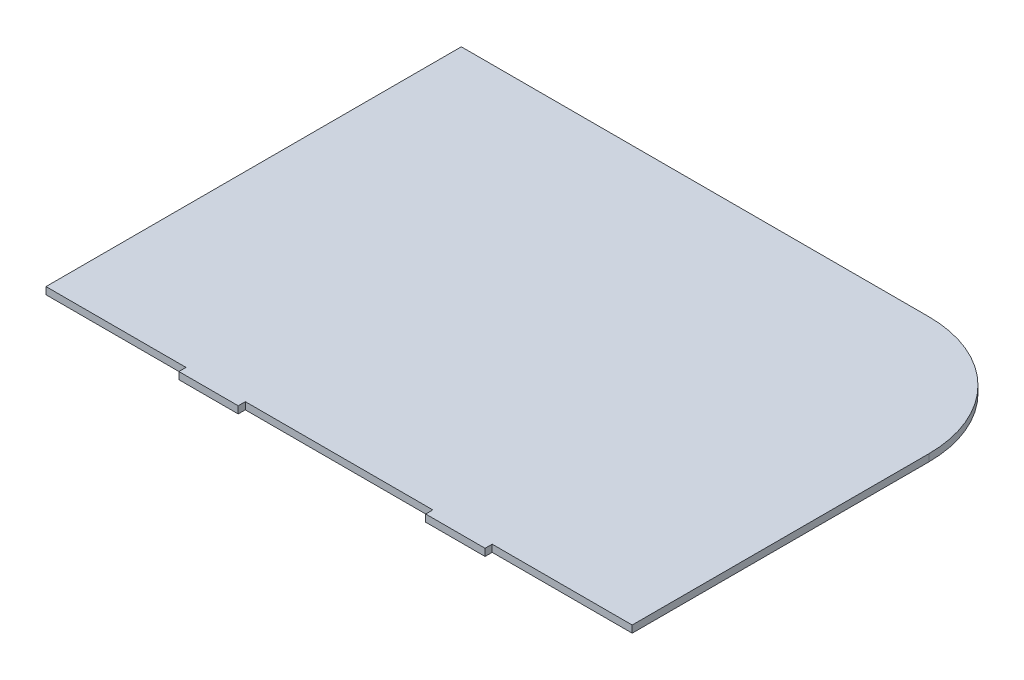
SolidWorks part; units mm, degrees
material "Maple"
ref_plane "Front Plane" through (0, 0, 0) normal (0, 0, 1) x (1, 0, 0)
ref_plane "Top Plane" through (0, 0, 0) normal (0, 1, 0) x (1, 0, 0)
ref_plane "Right Plane" through (0, 0, 0) normal (1, 0, 0) x (0, 0, -1)
sketch "Sketch1" plane through (0, 0, 0) normal (0, 1, 0) x (1, 0, 0)
  line L0 (54.0641, -230.8649) -> (54.0641, -236.8649)
  line L1 (-271.9359, 119.1351) -> (122.0641, 119.1351)
  line L2 (-271.9359, 119.1351) -> (-271.9359, -230.8649)
  line L3 (-271.9359, -230.8649) -> (-153.9359, -230.8649)
  line L5 (54.0641, -236.8649) -> (104.0641, -236.8649)
  line L6 (104.0641, -236.8649) -> (104.0641, -230.8649)
  line L8 (104.0641, -230.8649) -> (222.0641, -230.8649)
  line L13 (222.0641, -230.8649) -> (222.0641, 19.1351)
  line L21 (-153.9359, -230.8649) -> (-153.9359, -236.8649)
  line L22 (-153.9359, -236.8649) -> (-103.9359, -236.8649)
  line L23 (-103.9359, -230.8649) -> (-103.9359, -236.8649)
  line L29 (-103.9359, -230.8649) -> (54.0641, -230.8649)
  arc A0 (222.0641, 19.1351) -> (122.0641, 119.1351) centre (122.0641, 19.1351) ccw
  point P0 (0, 0)
  dimension "D3" = 100
  dimension "D2" = 350
  dimension "D4" = 50
  dimension "D5" = 350
  dimension "D8" = 118
  dimension "D9" = 158
  dimension "D10" = 50
  dimension "D11" = 118
  dimension "D12" = 6
  dimension "D13" = 6
  dimension "D14" = 6
  dimension "D15" = 6
extrude "Boss-Extrude1" add sketch "Sketch1" along normal blind 6
